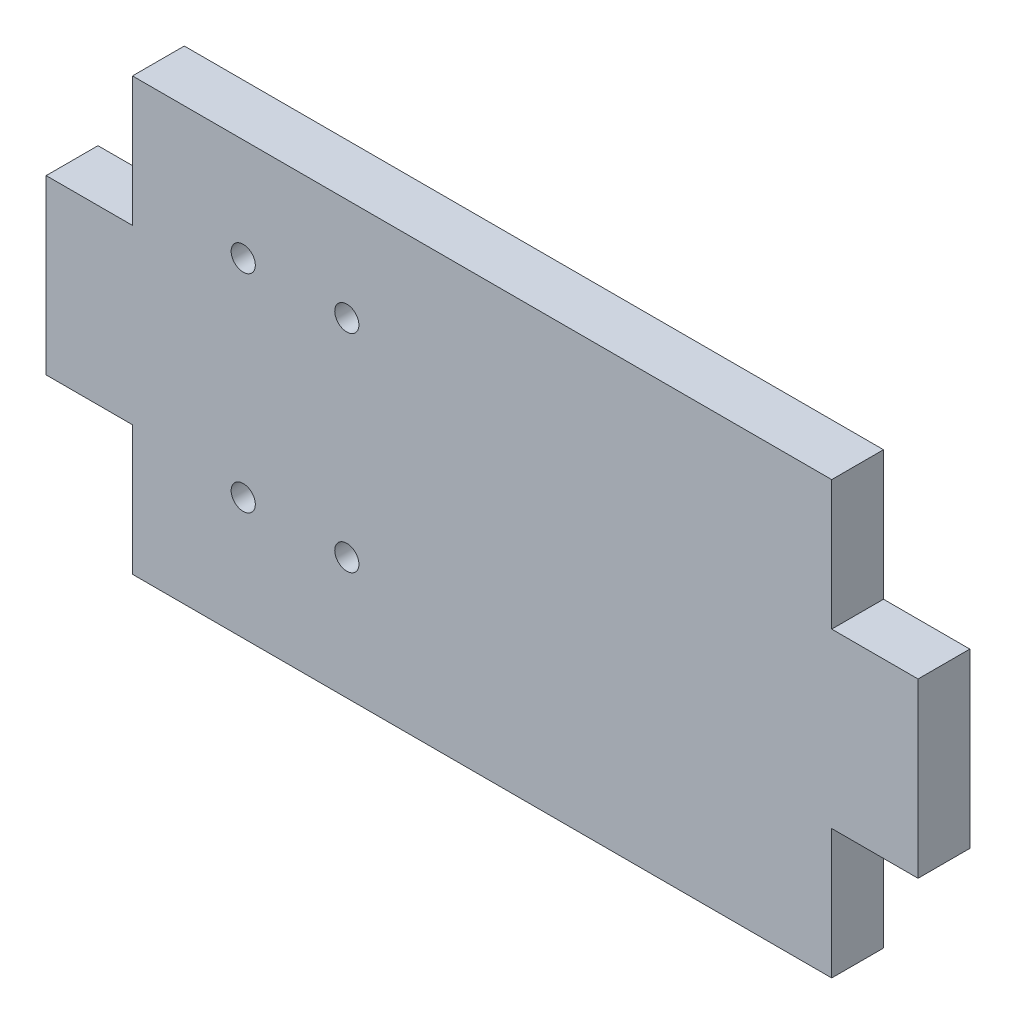
SolidWorks part; units mm, degrees
ref_plane "Plan de face" through (0, 0, 0) normal (0, 0, 1) x (1, 0, 0)
ref_plane "Plan de dessus" through (0, 0, 0) normal (0, 1, 0) x (1, 0, 0)
ref_plane "Plan de droite" through (0, 0, 0) normal (1, 0, 0) x (0, 0, -1)
sketch "Esquisse1" plane through (0, 0, 0) normal (0, 0, 1) x (1, 0, 0)
  line L1 (0, 0) -> (81, 0)
  line L2 (0, 0) -> (0, 50)
  line L3 (0, 50) -> (81, 50)
  line L4 (81, 0) -> (81, 50)
  line L5 (0, 35) -> (-10, 35)
  line L6 (0, 35) -> (0, 15)
  line L7 (0, 15) -> (-10, 15)
  line L8 (-10, 35) -> (-10, 15)
  line L9 (81, 35) -> (91, 35)
  line L10 (81, 35) -> (81, 15)
  line L11 (81, 15) -> (91, 15)
  line L12 (91, 35) -> (91, 15)
  point P13 (-10, 25)
  point P14 (0, 25)
  point P15 (91, 25)
  point P16 (81, 25)
  dimension "D1" = 81
  dimension "D2" = 50
  dimension "D3" = 10
  dimension "D4" = 20
  dimension "D5" = 10
  dimension "D6" = 20
extrude "Boss.-Extru.1" add sketch "Esquisse1" along normal blind 6 contours L5 L8 L7 L2 | L1 L4 L3 L2 | L12 L9 L4 L11
sketch "Esquisse2" plane through (0, 0, 0) normal (0, 0, -1) x (-1, 0, 0)
  line L0 (-24.8289, 38.1224) -> (-12.8289, 38.1224) construction
  line L1 (-12.8289, 38.1224) -> (-12.8289, 14.1224) construction
  line L2 (-12.8289, 14.1224) -> (-24.8289, 14.1224) construction
  line L3 (-24.8289, 14.1224) -> (-24.8289, 38.1224) construction
  line L4 (0, 50) -> (-81, 50) construction
  line L5 (0, 14.85) -> (0, 35.15) construction
  circle A0 centre (-12.8289, 14.1224) radius 1.4
  circle A1 centre (-12.8289, 38.1224) radius 1.4
  circle A2 centre (-24.8289, 38.1224) radius 1.4
  circle A3 centre (-24.8289, 14.1224) radius 1.4
  dimension "D1" = 11.8776
  dimension "D2" = 24
  dimension "D3" = 2.8
  dimension "D4" = 12.8289
  dimension "D6" = 12
extrude "Enlèv. mat.-Extru.1" cut sketch "Esquisse2" against normal up to surface (6 mm away) up to face at (40.5, 25, 6)
sketch "Esquisse3" plane through (0, 0, 0) normal (0, 0, -1) x (-1, 0, 0)
  circle A0 centre (-24.8289, 38.1224) radius 3
  circle A1 centre (-12.8289, 38.1224) radius 3
  circle A2 centre (-12.8289, 14.1224) radius 3
  circle A3 centre (-24.8289, 14.1224) radius 3
  dimension "D1" = 6
extrude "Enlèv. mat.-Extru.2" cut sketch "Esquisse3" against normal blind 4
